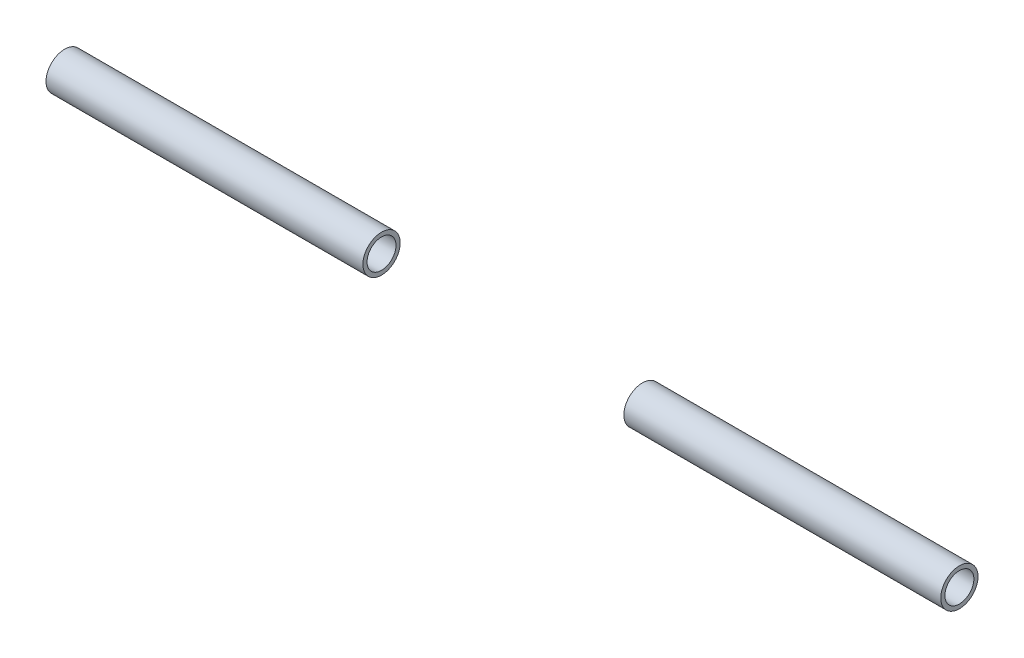
SolidWorks part; units mm, degrees
material "AISI 316 Annealed Stainless Steel Bar (SS)"
ref_plane "Front Plane" through (0, 0, 0) normal (0, 0, 1) x (1, 0, 0)
ref_plane "Top Plane" through (0, 0, 0) normal (0, 1, 0) x (1, 0, 0)
ref_plane "Right Plane" through (0, 0, 0) normal (1, 0, 0) x (0, 0, -1)
sketch "Sketch1" plane through (0, 0, 0) normal (0, 0, 1) x (1, 0, 0)
  line L0 (76.2, 2.4638) -> (76.2, -2.4638) construction
  line L1 (-76.2, 3.175) -> (76.2, 3.175) construction
  line L2 (-76.2, 3.175) -> (-76.2, 2.4638) construction
  line L3 (-76.2, 2.4638) -> (76.2, 2.4638) construction
  line L4 (76.2, 3.175) -> (76.2, 2.4638) construction
  line L5 (-76.2, -2.4638) -> (76.2, -2.4638) construction
  line L6 (-76.2, -2.4638) -> (-76.2, -3.175) construction
  line L7 (-76.2, -3.175) -> (76.2, -3.175) construction
  line L8 (76.2, -2.4638) -> (76.2, -3.175) construction
  line L9 (-76.2, 2.4638) -> (-76.2, -2.4638) construction
  line L10 (-76.2, 0) -> (76.2, 0) construction
  point P10 (-66.675, 0)
  point P12 (66.675, 0)
  dimension "OD" = 6.35
  dimension "ID" = 4.9276
  dimension "Wall Thickness" = 0.7112
  dimension "Length" = 152.4
  dimension "D5" = 9.525
  dimension "D6" = 9.525
sketch "Sketch2" plane through (0, 0, 0) normal (1, 0, 0) x (0, 0, -1)
  line L0 (0, 2.4638) -> (0, -2.4638) construction
  line L1 (-3.175, 0) -> (-2.4638, 0) construction
  line L2 (2.4638, 0) -> (3.175, 0) construction
  circle A0 centre (0, 0) radius 3.175 construction
  circle A1 centre (0, 0) radius 2.4638 construction
  dimension "OD" = 6.35
  dimension "ID" = 4.9276
sketch "Sketch3" plane through (0, 0, 0) normal (0, 0, 1) x (1, 0, 0)
  line L1 (-76.2, 3.175) -> (76.2, 3.175)
  line L2 (-76.2, 3.175) -> (-76.2, 2.4638)
  line L3 (-76.2, 2.4638) -> (76.2, 2.4638)
  line L4 (76.2, 3.175) -> (76.2, 2.4638)
revolve "Revolve1" add sketch "Sketch3" angle 360 about L10
sketch "Sketch4" plane through (0, 0, 0) normal (0, 0, 1) x (1, 0, 0)
  line L1 (-22.225, -22.225) -> (22.225, -22.225)
  line L2 (-22.225, -22.225) -> (-22.225, 22.225)
  line L3 (-22.225, 22.225) -> (22.225, 22.225)
  line L4 (22.225, -22.225) -> (22.225, 22.225)
  line L5 (-22.225, -22.225) -> (22.225, 22.225) construction
  line L6 (-22.225, 22.225) -> (22.225, -22.225) construction
  point P0 (0, 0)
  dimension "D1" = 44.45
extrude "Cut-Extrude1" cut sketch "Sketch4" against normal through all both and the other way through all
equation "\"D5@Sketch1\" = \"OD@Sketch1\" * 1.5"
equation "\"D6@Sketch1\" = \"OD@Sketch1\" * 1.5"
